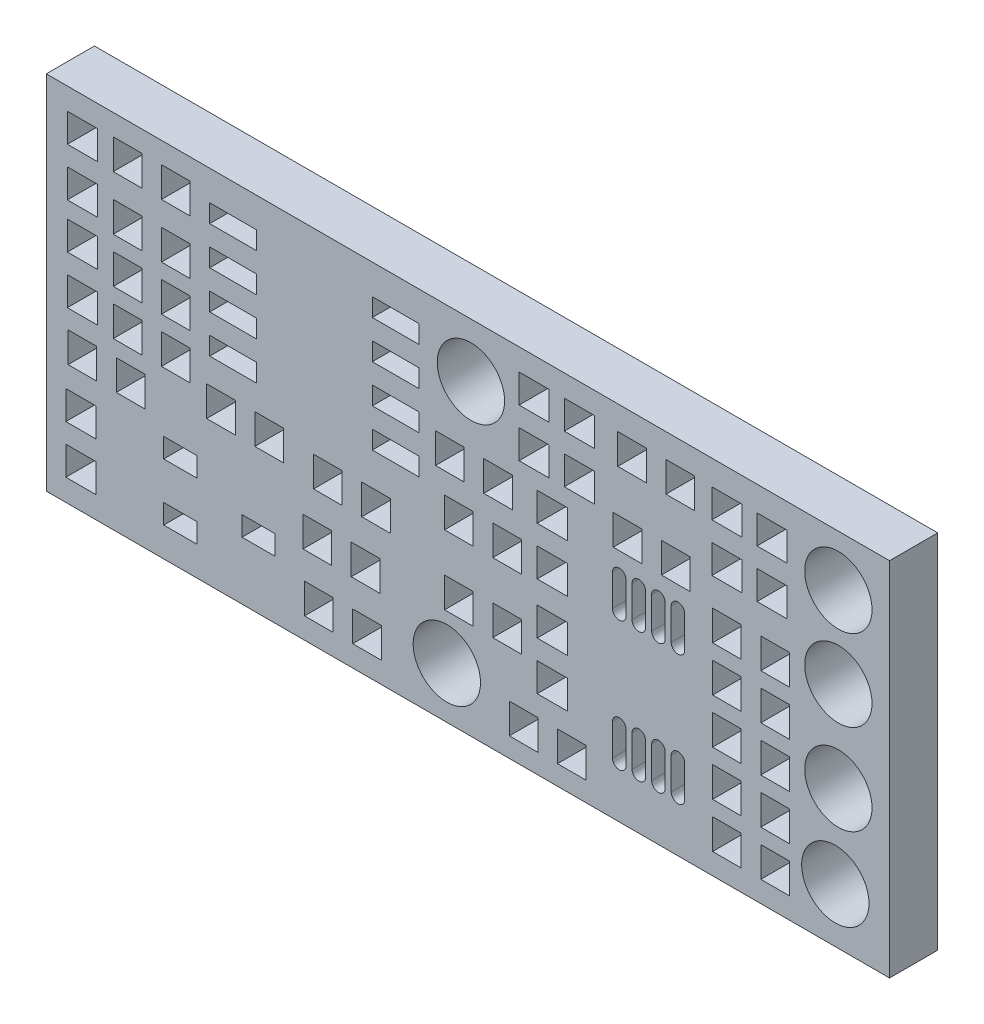
SolidWorks part; units mm, degrees
ref_plane "Plan de face" through (0, 0, 0) normal (0, 0, 1) x (1, 0, 0)
ref_plane "Plan de dessus" through (0, 0, 0) normal (0, 1, 0) x (1, 0, 0)
ref_plane "Plan de droite" through (0, 0, 0) normal (1, 0, 0) x (0, 0, -1)
sketch "Model" plane through (0, 0, 0) normal (0, 0, 1) x (1, 0, 0)
  line L0 (3.9, 2.875) -> (3.9, 3.525)
  line L1 (3.9, 3.525) -> (5, 3.525)
  line L2 (5, 3.525) -> (5, 2.875)
  line L3 (5, 2.875) -> (3.9, 2.875)
  line L4 (3.9, 0.975) -> (3.9, 1.625)
  line L5 (3.9, 1.625) -> (5, 1.625)
  line L6 (5, 1.625) -> (5, 0.975)
  line L7 (5, 0.975) -> (3.9, 0.975)
  line L8 (6.5, 1.925) -> (6.5, 2.575)
  line L9 (6.5, 2.575) -> (7.6, 2.575)
  line L10 (7.6, 2.575) -> (7.6, 1.925)
  line L11 (7.6, 1.925) -> (6.5, 1.925)
  line L12 (19.25, 2.775) -> (19.25, 1.725)
  line L13 (18.8, 1.725) -> (18.8, 2.775)
  line L14 (19.9, 2.775) -> (19.9, 1.725)
  line L15 (19.45, 1.725) -> (19.45, 2.775)
  line L16 (20.55, 2.775) -> (20.55, 1.725)
  line L17 (20.1, 1.725) -> (20.1, 2.775)
  line L18 (21.2, 2.775) -> (21.2, 1.725)
  line L19 (20.75, 1.725) -> (20.75, 2.775)
  line L20 (21.2, 7.075) -> (21.2, 6.025)
  line L21 (20.75, 6.025) -> (20.75, 7.075)
  line L22 (20.55, 7.075) -> (20.55, 6.025)
  line L23 (20.1, 6.025) -> (20.1, 7.075)
  line L24 (19.9, 7.075) -> (19.9, 6.025)
  line L25 (19.45, 6.025) -> (19.45, 7.075)
  line L26 (19.25, 7.075) -> (19.25, 6.025)
  line L27 (18.8, 6.025) -> (18.8, 7.075)
  line L28 (12.375, 7.195) -> (12.375, 6.595)
  line L29 (12.375, 6.595) -> (10.825, 6.595)
  line L30 (10.825, 6.595) -> (10.825, 7.195)
  line L31 (10.825, 7.195) -> (12.375, 7.195)
  line L32 (12.375, 8.465) -> (12.375, 7.865)
  line L33 (12.375, 7.865) -> (10.825, 7.865)
  line L34 (10.825, 7.865) -> (10.825, 8.465)
  line L35 (10.825, 8.465) -> (12.375, 8.465)
  line L36 (12.375, 9.735) -> (12.375, 9.135)
  line L37 (12.375, 9.135) -> (10.825, 9.135)
  line L38 (10.825, 9.135) -> (10.825, 9.735)
  line L39 (10.825, 9.735) -> (12.375, 9.735)
  line L40 (12.375, 11.005) -> (12.375, 10.405)
  line L41 (12.375, 10.405) -> (10.825, 10.405)
  line L42 (10.825, 10.405) -> (10.825, 11.005)
  line L43 (10.825, 11.005) -> (12.375, 11.005)
  line L44 (6.975, 11.005) -> (6.975, 10.405)
  line L45 (6.975, 10.405) -> (5.425, 10.405)
  line L46 (5.425, 10.405) -> (5.425, 11.005)
  line L47 (5.425, 11.005) -> (6.975, 11.005)
  line L48 (6.975, 9.735) -> (6.975, 9.135)
  line L49 (6.975, 9.135) -> (5.425, 9.135)
  line L50 (5.425, 9.135) -> (5.425, 9.735)
  line L51 (5.425, 9.735) -> (6.975, 9.735)
  line L52 (6.975, 8.465) -> (6.975, 7.865)
  line L53 (6.975, 7.865) -> (5.425, 7.865)
  line L54 (5.425, 7.865) -> (5.425, 8.465)
  line L55 (5.425, 8.465) -> (6.975, 8.465)
  line L56 (6.975, 7.195) -> (6.975, 6.595)
  line L57 (6.975, 6.595) -> (5.425, 6.595)
  line L58 (5.425, 6.595) -> (5.425, 7.195)
  line L59 (5.425, 7.195) -> (6.975, 7.195)
  line L60 (20.575, 11.2) -> (21.525, 11.2)
  line L61 (21.525, 11.2) -> (21.525, 10.2)
  line L62 (21.525, 10.2) -> (20.575, 10.2)
  line L63 (20.575, 10.2) -> (20.575, 11.2)
  line L64 (18.975, 11.2) -> (19.925, 11.2)
  line L65 (19.925, 11.2) -> (19.925, 10.2)
  line L66 (19.925, 10.2) -> (18.975, 10.2)
  line L67 (18.975, 10.2) -> (18.975, 11.2)
  line L68 (23.075, 5.2) -> (22.125, 5.2)
  line L69 (22.125, 5.2) -> (22.125, 6.2)
  line L70 (22.125, 6.2) -> (23.075, 6.2)
  line L71 (23.075, 6.2) -> (23.075, 5.2)
  line L72 (24.675, 5.2) -> (23.725, 5.2)
  line L73 (23.725, 5.2) -> (23.725, 6.2)
  line L74 (23.725, 6.2) -> (24.675, 6.2)
  line L75 (24.675, 6.2) -> (24.675, 5.2)
  line L76 (16.325, 0.65) -> (15.375, 0.65)
  line L77 (15.375, 0.65) -> (15.375, 1.65)
  line L78 (15.375, 1.65) -> (16.325, 1.65)
  line L79 (16.325, 1.65) -> (16.325, 0.65)
  line L80 (17.925, 0.65) -> (16.975, 0.65)
  line L81 (16.975, 0.65) -> (16.975, 1.65)
  line L82 (16.975, 1.65) -> (17.925, 1.65)
  line L83 (17.925, 1.65) -> (17.925, 0.65)
  line L84 (17.3, 6.575) -> (17.3, 5.625)
  line L85 (17.3, 5.625) -> (16.3, 5.625)
  line L86 (16.3, 5.625) -> (16.3, 6.575)
  line L87 (16.3, 6.575) -> (17.3, 6.575)
  line L88 (17.3, 8.175) -> (17.3, 7.225)
  line L89 (17.3, 7.225) -> (16.3, 7.225)
  line L90 (16.3, 7.225) -> (16.3, 8.175)
  line L91 (16.3, 8.175) -> (17.3, 8.175)
  line L92 (16.3, 3.925) -> (16.3, 4.875)
  line L93 (16.3, 4.875) -> (17.3, 4.875)
  line L94 (17.3, 4.875) -> (17.3, 3.925)
  line L95 (17.3, 3.925) -> (16.3, 3.925)
  line L96 (16.3, 2.325) -> (16.3, 3.275)
  line L97 (16.3, 3.275) -> (17.3, 3.275)
  line L98 (17.3, 3.275) -> (17.3, 2.325)
  line L99 (17.3, 2.325) -> (16.3, 2.325)
  line L100 (19.775, 7.8) -> (18.825, 7.8)
  line L101 (18.825, 7.8) -> (18.825, 8.8)
  line L102 (18.825, 8.8) -> (19.775, 8.8)
  line L103 (19.775, 8.8) -> (19.775, 7.8)
  line L104 (21.375, 7.8) -> (20.425, 7.8)
  line L105 (20.425, 7.8) -> (20.425, 8.8)
  line L106 (20.425, 8.8) -> (21.375, 8.8)
  line L107 (21.375, 8.8) -> (21.375, 7.8)
  line L108 (23.725, 7.7) -> (24.675, 7.7)
  line L109 (24.675, 7.7) -> (24.675, 6.7)
  line L110 (24.675, 6.7) -> (23.725, 6.7)
  line L111 (23.725, 6.7) -> (23.725, 7.7)
  line L112 (22.125, 7.7) -> (23.075, 7.7)
  line L113 (23.075, 7.7) -> (23.075, 6.7)
  line L114 (23.075, 6.7) -> (22.125, 6.7)
  line L115 (22.125, 6.7) -> (22.125, 7.7)
  line L116 (14.825, 6.5) -> (15.775, 6.5)
  line L117 (15.775, 6.5) -> (15.775, 5.5)
  line L118 (15.775, 5.5) -> (14.825, 5.5)
  line L119 (14.825, 5.5) -> (14.825, 6.5)
  line L120 (13.225, 6.5) -> (14.175, 6.5)
  line L121 (14.175, 6.5) -> (14.175, 5.5)
  line L122 (14.175, 5.5) -> (13.225, 5.5)
  line L123 (13.225, 5.5) -> (13.225, 6.5)
  line L124 (14.825, 4.2) -> (15.775, 4.2)
  line L125 (15.775, 4.2) -> (15.775, 3.2)
  line L126 (15.775, 3.2) -> (14.825, 3.2)
  line L127 (14.825, 3.2) -> (14.825, 4.2)
  line L128 (13.225, 4.2) -> (14.175, 4.2)
  line L129 (14.175, 4.2) -> (14.175, 3.2)
  line L130 (14.175, 3.2) -> (13.225, 3.2)
  line L131 (13.225, 3.2) -> (13.225, 4.2)
  line L132 (23.075, 3.7) -> (22.125, 3.7)
  line L133 (22.125, 3.7) -> (22.125, 4.7)
  line L134 (22.125, 4.7) -> (23.075, 4.7)
  line L135 (23.075, 4.7) -> (23.075, 3.7)
  line L136 (24.675, 3.7) -> (23.725, 3.7)
  line L137 (23.725, 3.7) -> (23.725, 4.7)
  line L138 (23.725, 4.7) -> (24.675, 4.7)
  line L139 (24.675, 4.7) -> (24.675, 3.7)
  line L140 (23.075, 2.2) -> (22.125, 2.2)
  line L141 (22.125, 2.2) -> (22.125, 3.2)
  line L142 (22.125, 3.2) -> (23.075, 3.2)
  line L143 (23.075, 3.2) -> (23.075, 2.2)
  line L144 (24.675, 2.2) -> (23.725, 2.2)
  line L145 (23.725, 2.2) -> (23.725, 3.2)
  line L146 (23.725, 3.2) -> (24.675, 3.2)
  line L147 (24.675, 3.2) -> (24.675, 2.2)
  line L148 (23.725, 1.7) -> (24.675, 1.7)
  line L149 (24.675, 1.7) -> (24.675, 0.7)
  line L150 (24.675, 0.7) -> (23.725, 0.7)
  line L151 (23.725, 0.7) -> (23.725, 1.7)
  line L152 (22.125, 1.7) -> (23.075, 1.7)
  line L153 (23.075, 1.7) -> (23.075, 0.7)
  line L154 (23.075, 0.7) -> (22.125, 0.7)
  line L155 (22.125, 0.7) -> (22.125, 1.7)
  line L156 (18.2, 9.675) -> (18.2, 8.725)
  line L157 (18.2, 8.725) -> (17.2, 8.725)
  line L158 (17.2, 8.725) -> (17.2, 9.675)
  line L159 (17.2, 9.675) -> (18.2, 9.675)
  line L160 (18.2, 11.275) -> (18.2, 10.325)
  line L161 (18.2, 10.325) -> (17.2, 10.325)
  line L162 (17.2, 10.325) -> (17.2, 11.275)
  line L163 (17.2, 11.275) -> (18.2, 11.275)
  line L164 (23.1, 9.575) -> (23.1, 8.625)
  line L165 (23.1, 8.625) -> (22.1, 8.625)
  line L166 (22.1, 8.625) -> (22.1, 9.575)
  line L167 (22.1, 9.575) -> (23.1, 9.575)
  line L168 (23.1, 11.175) -> (23.1, 10.225)
  line L169 (23.1, 10.225) -> (22.1, 10.225)
  line L170 (22.1, 10.225) -> (22.1, 11.175)
  line L171 (22.1, 11.175) -> (23.1, 11.175)
  line L172 (23.6, 10.225) -> (23.6, 11.175)
  line L173 (23.6, 11.175) -> (24.6, 11.175)
  line L174 (24.6, 11.175) -> (24.6, 10.225)
  line L175 (24.6, 10.225) -> (23.6, 10.225)
  line L176 (23.6, 8.625) -> (23.6, 9.575)
  line L177 (23.6, 9.575) -> (24.6, 9.575)
  line L178 (24.6, 9.575) -> (24.6, 8.625)
  line L179 (24.6, 8.625) -> (23.6, 8.625)
  line L180 (1.7, 9.675) -> (1.7, 8.725)
  line L181 (1.7, 8.725) -> (0.7, 8.725)
  line L182 (0.7, 8.725) -> (0.7, 9.675)
  line L183 (0.7, 9.675) -> (1.7, 9.675)
  line L184 (1.7, 11.275) -> (1.7, 10.325)
  line L185 (1.7, 10.325) -> (0.7, 10.325)
  line L186 (0.7, 10.325) -> (0.7, 11.275)
  line L187 (0.7, 11.275) -> (1.7, 11.275)
  line L188 (15.7, 10.325) -> (15.7, 11.275)
  line L189 (15.7, 11.275) -> (16.7, 11.275)
  line L190 (16.7, 11.275) -> (16.7, 10.325)
  line L191 (16.7, 10.325) -> (15.7, 10.325)
  line L192 (15.7, 8.725) -> (15.7, 9.675)
  line L193 (15.7, 9.675) -> (16.7, 9.675)
  line L194 (16.7, 9.675) -> (16.7, 8.725)
  line L195 (16.7, 8.725) -> (15.7, 8.725)
  line L196 (0.7, 7.225) -> (0.7, 8.175)
  line L197 (0.7, 8.175) -> (1.7, 8.175)
  line L198 (1.7, 8.175) -> (1.7, 7.225)
  line L199 (1.7, 7.225) -> (0.7, 7.225)
  line L200 (0.7, 5.625) -> (0.7, 6.575)
  line L201 (0.7, 6.575) -> (1.7, 6.575)
  line L202 (1.7, 6.575) -> (1.7, 5.625)
  line L203 (1.7, 5.625) -> (0.7, 5.625)
  line L204 (10.175, 1.7) -> (11.125, 1.7)
  line L205 (11.125, 1.7) -> (11.125, 0.7)
  line L206 (11.125, 0.7) -> (10.175, 0.7)
  line L207 (10.175, 0.7) -> (10.175, 1.7)
  line L208 (8.575, 1.7) -> (9.525, 1.7)
  line L209 (9.525, 1.7) -> (9.525, 0.7)
  line L210 (9.525, 0.7) -> (8.575, 0.7)
  line L211 (8.575, 0.7) -> (8.575, 1.7)
  line L212 (3.825, 11.3) -> (4.775, 11.3)
  line L213 (4.775, 11.3) -> (4.775, 10.3)
  line L214 (4.775, 10.3) -> (3.825, 10.3)
  line L215 (3.825, 10.3) -> (3.825, 11.3)
  line L216 (2.225, 11.3) -> (3.175, 11.3)
  line L217 (3.175, 11.3) -> (3.175, 10.3)
  line L218 (3.175, 10.3) -> (2.225, 10.3)
  line L219 (2.225, 10.3) -> (2.225, 11.3)
  line L220 (1.65, 1.675) -> (1.65, 0.725)
  line L221 (1.65, 0.725) -> (0.65, 0.725)
  line L222 (0.65, 0.725) -> (0.65, 1.675)
  line L223 (0.65, 1.675) -> (1.65, 1.675)
  line L224 (1.65, 3.275) -> (1.65, 2.325)
  line L225 (1.65, 2.325) -> (0.65, 2.325)
  line L226 (0.65, 2.325) -> (0.65, 3.275)
  line L227 (0.65, 3.275) -> (1.65, 3.275)
  line L228 (14.525, 8.2) -> (15.475, 8.2)
  line L229 (15.475, 8.2) -> (15.475, 7.2)
  line L230 (15.475, 7.2) -> (14.525, 7.2)
  line L231 (14.525, 7.2) -> (14.525, 8.2)
  line L232 (12.925, 8.2) -> (13.875, 8.2)
  line L233 (13.875, 8.2) -> (13.875, 7.2)
  line L234 (13.875, 7.2) -> (12.925, 7.2)
  line L235 (12.925, 7.2) -> (12.925, 8.2)
  line L236 (6.275, 4.75) -> (5.325, 4.75)
  line L237 (5.325, 4.75) -> (5.325, 5.75)
  line L238 (5.325, 5.75) -> (6.275, 5.75)
  line L239 (6.275, 5.75) -> (6.275, 4.75)
  line L240 (7.875, 4.75) -> (6.925, 4.75)
  line L241 (6.925, 4.75) -> (6.925, 5.75)
  line L242 (6.925, 5.75) -> (7.875, 5.75)
  line L243 (7.875, 5.75) -> (7.875, 4.75)
  line L244 (2.325, 5) -> (3.275, 5)
  line L245 (3.275, 5) -> (3.275, 4)
  line L246 (3.275, 4) -> (2.325, 4)
  line L247 (2.325, 4) -> (2.325, 5)
  line L248 (0.725, 5) -> (1.675, 5)
  line L249 (1.675, 5) -> (1.675, 4)
  line L250 (1.675, 4) -> (0.725, 4)
  line L251 (0.725, 4) -> (0.725, 5)
  line L252 (10.125, 3.6) -> (11.075, 3.6)
  line L253 (11.075, 3.6) -> (11.075, 2.6)
  line L254 (11.075, 2.6) -> (10.125, 2.6)
  line L255 (10.125, 2.6) -> (10.125, 3.6)
  line L256 (8.525, 3.6) -> (9.475, 3.6)
  line L257 (9.475, 3.6) -> (9.475, 2.6)
  line L258 (9.475, 2.6) -> (8.525, 2.6)
  line L259 (8.525, 2.6) -> (8.525, 3.6)
  line L260 (9.825, 4.5) -> (8.875, 4.5)
  line L261 (8.875, 4.5) -> (8.875, 5.5)
  line L262 (8.875, 5.5) -> (9.825, 5.5)
  line L263 (9.825, 5.5) -> (9.825, 4.5)
  line L264 (11.425, 4.5) -> (10.475, 4.5)
  line L265 (10.475, 4.5) -> (10.475, 5.5)
  line L266 (10.475, 5.5) -> (11.425, 5.5)
  line L267 (11.425, 5.5) -> (11.425, 4.5)
  line L268 (3.175, 7) -> (2.225, 7)
  line L269 (2.225, 7) -> (2.225, 8)
  line L270 (2.225, 8) -> (3.175, 8)
  line L271 (3.175, 8) -> (3.175, 7)
  line L272 (4.775, 7) -> (3.825, 7)
  line L273 (3.825, 7) -> (3.825, 8)
  line L274 (3.825, 8) -> (4.775, 8)
  line L275 (4.775, 8) -> (4.775, 7)
  line L276 (3.175, 8.5) -> (2.225, 8.5)
  line L277 (2.225, 8.5) -> (2.225, 9.5)
  line L278 (2.225, 9.5) -> (3.175, 9.5)
  line L279 (3.175, 9.5) -> (3.175, 8.5)
  line L280 (4.775, 8.5) -> (3.825, 8.5)
  line L281 (3.825, 8.5) -> (3.825, 9.5)
  line L282 (3.825, 9.5) -> (4.775, 9.5)
  line L283 (4.775, 9.5) -> (4.775, 8.5)
  line L284 (3.825, 6.5) -> (4.775, 6.5)
  line L285 (4.775, 6.5) -> (4.775, 5.5)
  line L286 (4.775, 5.5) -> (3.825, 5.5)
  line L287 (3.825, 5.5) -> (3.825, 6.5)
  line L288 (2.225, 6.5) -> (3.175, 6.5)
  line L289 (3.175, 6.5) -> (3.175, 5.5)
  line L290 (3.175, 5.5) -> (2.225, 5.5)
  line L291 (2.225, 5.5) -> (2.225, 6.5)
  line L292 (0, 0) -> (0, 12)
  line L293 (0, 12) -> (28, 12)
  line L294 (28, 12) -> (28, 0)
  line L295 (28, 0) -> (0, 0)
  circle A0 centre (26.3, 10.3) radius 1.1176
  circle A1 centre (26.3, 10.3) radius 1.1176
  circle A2 centre (26.3, 7.6) radius 1.1176
  circle A3 centre (26.3, 7.6) radius 1.1176
  circle A4 centre (26.2, 1.8) radius 1.1176
  circle A5 centre (26.2, 1.8) radius 1.1176
  circle A6 centre (26.3, 4.6) radius 1.1176
  circle A7 centre (26.3, 4.6) radius 1.1176
  circle A8 centre (13.3, 1.7) radius 1.1176
  circle A9 centre (13.3, 1.7) radius 1.1176
  circle A10 centre (14.1, 10.2) radius 1.1176
  circle A11 centre (14.1, 10.2) radius 1.1176
  arc A12 (18.8, 1.725) -> (19.25, 1.725) centre (19.025, 1.725) ccw
  arc A13 (19.25, 2.775) -> (18.8, 2.775) centre (19.025, 2.775) ccw
  arc A14 (19.45, 1.725) -> (19.9, 1.725) centre (19.675, 1.725) ccw
  arc A15 (19.9, 2.775) -> (19.45, 2.775) centre (19.675, 2.775) ccw
  arc A16 (20.1, 1.725) -> (20.55, 1.725) centre (20.325, 1.725) ccw
  arc A17 (20.55, 2.775) -> (20.1, 2.775) centre (20.325, 2.775) ccw
  arc A18 (20.75, 1.725) -> (21.2, 1.725) centre (20.975, 1.725) ccw
  arc A19 (21.2, 2.775) -> (20.75, 2.775) centre (20.975, 2.775) ccw
  arc A20 (20.75, 6.025) -> (21.2, 6.025) centre (20.975, 6.025) ccw
  arc A21 (21.2, 7.075) -> (20.75, 7.075) centre (20.975, 7.075) ccw
  arc A22 (20.1, 6.025) -> (20.55, 6.025) centre (20.325, 6.025) ccw
  arc A23 (20.55, 7.075) -> (20.1, 7.075) centre (20.325, 7.075) ccw
  arc A24 (19.45, 6.025) -> (19.9, 6.025) centre (19.675, 6.025) ccw
  arc A25 (19.9, 7.075) -> (19.45, 7.075) centre (19.675, 7.075) ccw
  arc A26 (18.8, 6.025) -> (19.25, 6.025) centre (19.025, 6.025) ccw
  arc A27 (19.25, 7.075) -> (18.8, 7.075) centre (19.025, 7.075) ccw
extrude "Boss.-Extru.1" add sketch "Model" along normal blind 1.6 contours L295 L294 L293 L292 A27 L26 A26 L27 A25 L24 A24 L25 A23 L22 A22 L23 A21 L20 A20 L21 A19 L18 A18 L19 A17 L16 A16 L17 A15 L14 A14 L15 A13 L12 A12 L13 A10 A8 A6
